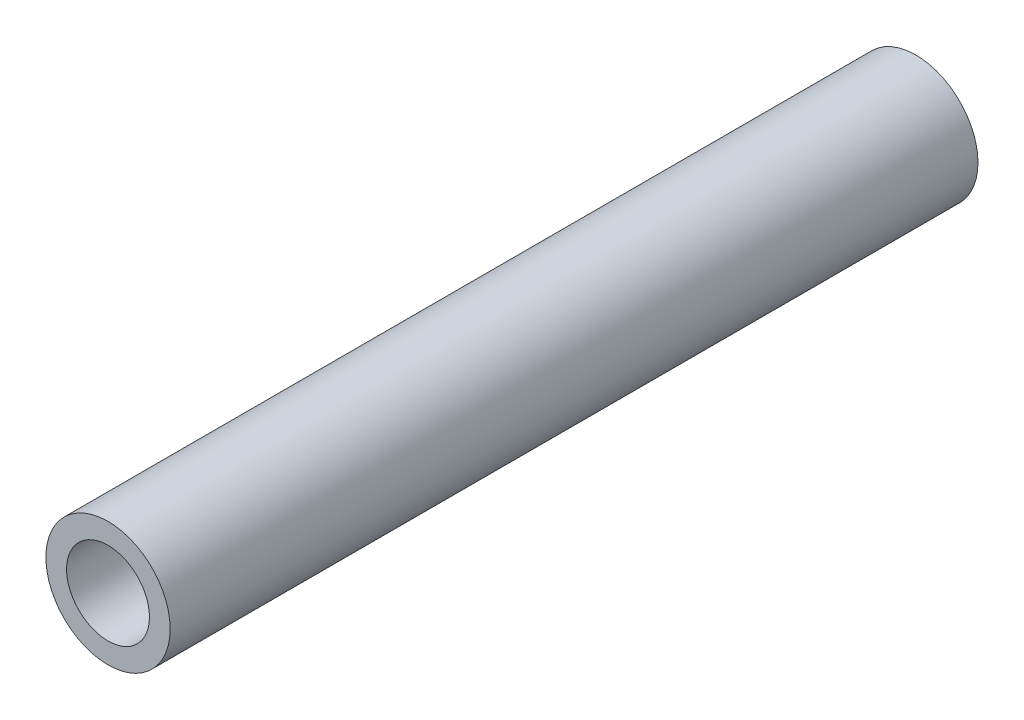
SolidWorks part; units mm, degrees
ref_plane "Front" through (0, 0, 0) normal (0, 0, 1) x (1, 0, 0)
ref_plane "Top" through (0, 0, 0) normal (0, 1, 0) x (1, 0, 0)
ref_plane "Right" through (0, 0, 0) normal (1, 0, 0) x (0, 0, -1)
sketch "Esquisse1" plane through (0, 0, 0) normal (0, 0, 1) x (1, 0, 0)
  circle A0 centre (0, 0) radius 3
  dimension "D1" = 6
extrude "Extru.-Mince1" add sketch "Esquisse1" along normal mid plane 39 thin thin type one direction reverse wall 1
